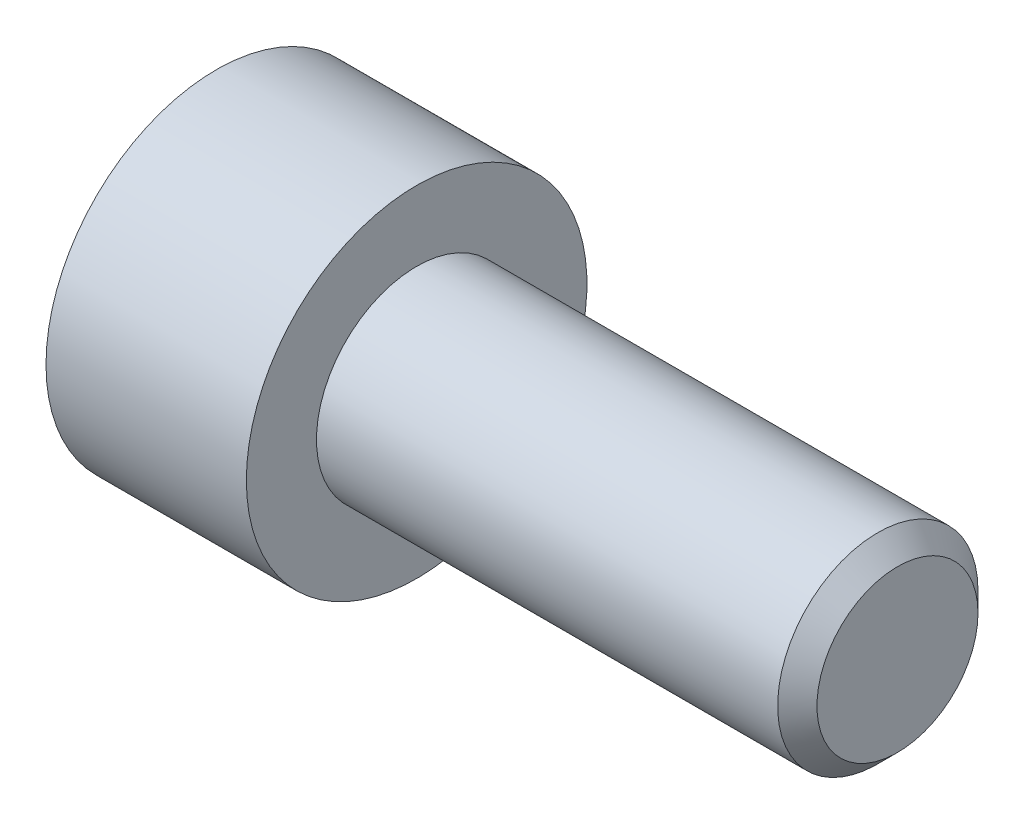
SolidWorks part; units mm, degrees
ref_plane "Front Plane" through (0, 0, 0) normal (0, 0, 1) x (1, 0, 0)
ref_plane "Top Plane" through (0, 0, 0) normal (0, 1, 0) x (1, 0, 0)
ref_plane "Right Plane" through (0, 0, 0) normal (1, 0, 0) x (0, 0, -1)
ref_plane "Plane1" through (0, 0, 0) normal (0, 0, -1) x (-1, 0, 0)
sketch "Sketch1" plane through (0, 0, 0) normal (0, 0, -1) x (-1, 0, 0)
  line L0 (0, 4.25) -> (0, 0)
  line L1 (0, 0) -> (5, 0)
  line L2 (5, 0) -> (5, 4.25)
  line L3 (5, 4.25) -> (0, 4.25)
  line L4 (0, 0) -> (5, 0) construction
revolve "Revolve1" add sketch "Sketch1" angle 360 about L4
sketch "Sketch2" plane through (0, 0, 0) normal (1, 0, 0) x (0, 0, -1)
  circle A0 centre (0, 0) radius 2.5
extrude "Boss-Extrude1" add sketch "Sketch2" along normal blind 12
sketch "Sketch3" plane through (-5, 0, 0) normal (-1, 0, 0) x (0, 0, 1)
  line L0 (2, 1.1547) -> (0, 2.3094)
  line L1 (0, 2.3094) -> (-2, 1.1547)
  line L2 (-2, 1.1547) -> (-2, -1.1547)
  line L3 (-2, -1.1547) -> (0, -2.3094)
  line L4 (0, -2.3094) -> (2, -1.1547)
  line L5 (2, -1.1547) -> (2, 1.1547)
extrude "Cut-Extrude1" cut sketch "Sketch3" against normal blind 2.5
sketch "Sketch4" plane through (0, 0, 0) normal (0, 0, 1) x (1, 0, 0)
  line L0 (-2.5, 1.99) -> (-2.5, 0)
  line L1 (-2.5, 0) -> (-1.3511, 0)
  line L2 (-1.3511, 0) -> (-2.5, 1.99)
  line L3 (-2.5, 0) -> (-1.351, 0) construction
revolve "Cut-Revolve1" cut sketch "Sketch4" angle 360 about L3
chamfer "Chamfer1" distance 0.4905 angle 45 1 edges at (12, 0, -2.5)
